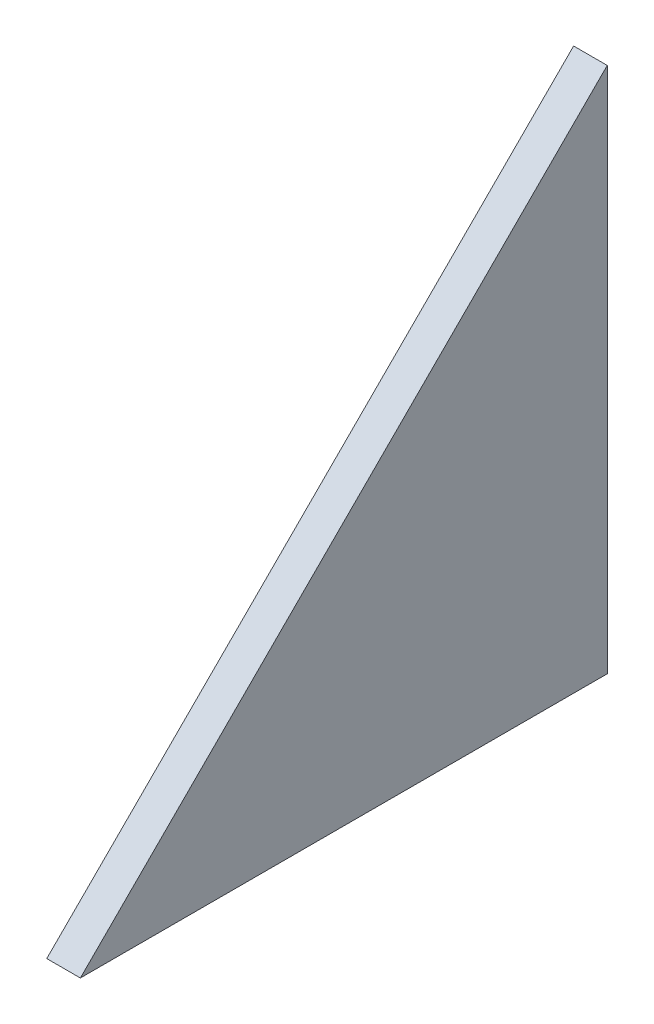
SolidWorks part; units mm, degrees
material "Perspex (TM) GS Acrylic Cast Sheet"
ref_plane "Front Plane" through (0, 0, 0) normal (0, 0, 1) x (1, 0, 0)
ref_plane "Top Plane" through (0, 0, 0) normal (0, 1, 0) x (1, 0, 0)
ref_plane "Right Plane" through (0, 0, 0) normal (1, 0, 0) x (0, 0, -1)
sketch "Sketch1" plane through (223.8446, 0, 0) normal (1, 0, 0) x (0, 0, -1)
  line L2 (-99.9922, 115.6349) -> (-99.9922, 68.6349)
  line L16 (-146.9922, 68.6349) -> (-99.9922, 115.6349)
  line L17 (-146.9922, 68.6349) -> (-99.9922, 68.6349)
extrude "Boss-Extrude1" add sketch "Sketch1" along normal blind 3
